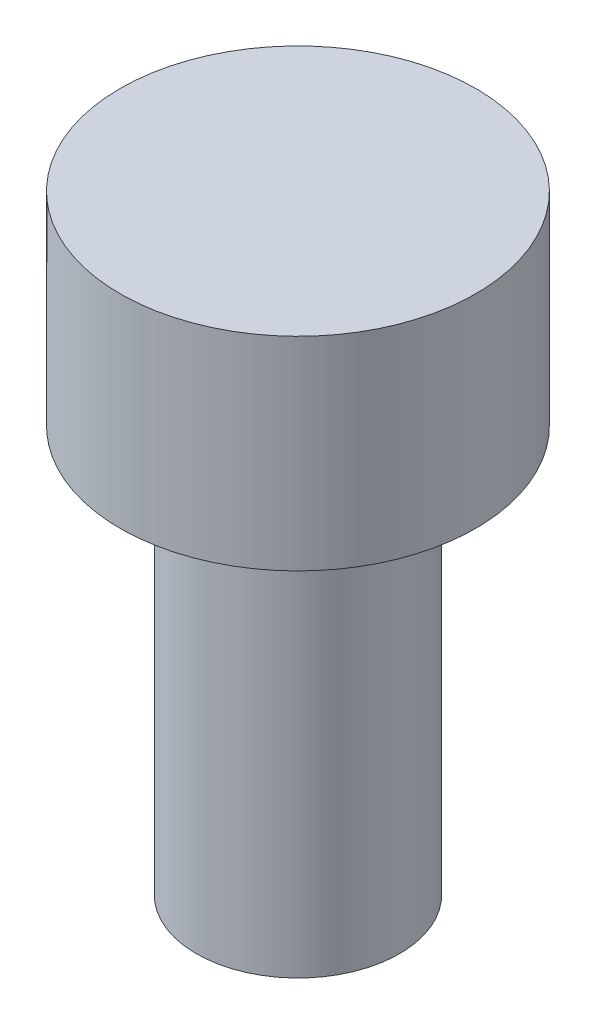
SolidWorks part; units mm, degrees
ref_plane "Front Plane" through (0, 0, 0) normal (0, 0, 1) x (1, 0, 0)
ref_plane "Top Plane" through (0, 0, 0) normal (0, 1, 0) x (1, 0, 0)
ref_plane "Right Plane" through (0, 0, 0) normal (1, 0, 0) x (0, 0, -1)
sketch "Sketch1" plane through (0, 0, 0) normal (0, 0, 1) x (1, 0, 0)
  line L0 (0, 12) -> (0, 0)
  line L1 (0, 0) -> (2, 0)
  line L2 (2, 0) -> (2, 8)
  line L3 (2, 8) -> (3.5, 8)
  line L4 (3.5, 8) -> (3.5, 12)
  line L5 (3.5, 12) -> (0, 12)
  dimension "D1" = 2
  dimension "D2" = 3.5
  dimension "D3" = 4
  dimension "D4" = 8
revolve "Revolve1" add sketch "Sketch1" angle 360 about L0
